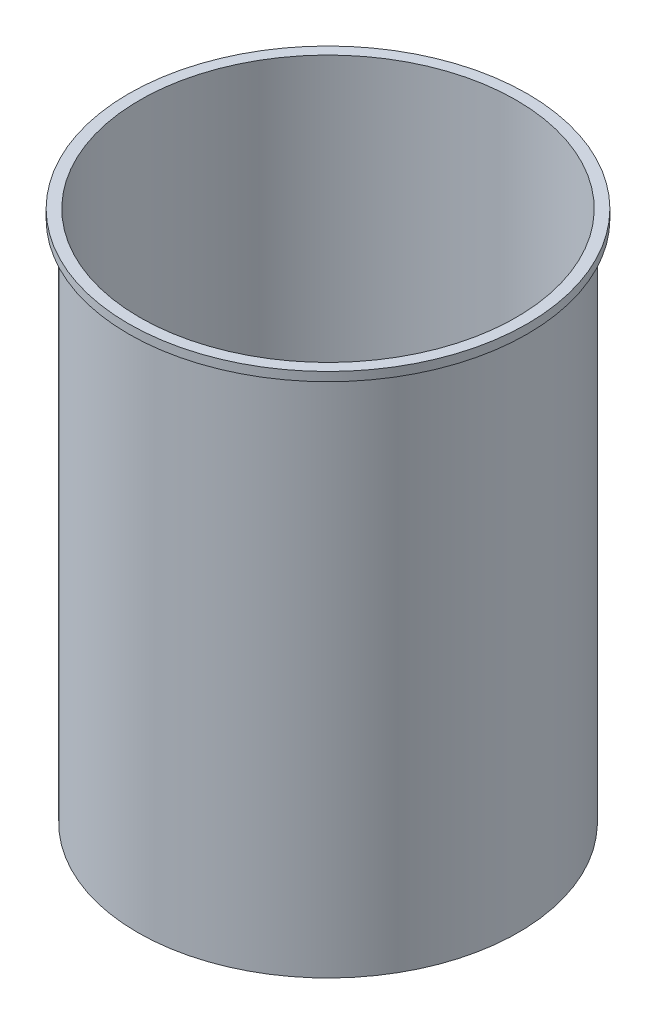
SolidWorks part; units mm, degrees
ref_plane "Front Plane" through (0, 0, 0) normal (0, 0, 1) x (1, 0, 0)
ref_plane "Top Plane" through (0, 0, 0) normal (0, 1, 0) x (1, 0, 0)
ref_plane "Right Plane" through (0, 0, 0) normal (1, 0, 0) x (0, 0, -1)
sketch "Sketch1" plane through (0, 0, 0) normal (0, 1, 0) x (1, 0, 0)
  circle A0 centre (0, 0) radius 42.5
  circle A1 centre (0, 0) radius 43
  dimension "D1" = 85
  dimension "D2" = 0.5
extrude "Boss-Extrude1" add sketch "Sketch1" along normal blind 118
sketch "Sketch2" plane through (0, 118, 0) normal (0, 1, 0) x (1, 0, 0)
  circle A0 centre (0, 0) radius 45
  circle A1 centre (0, 0) radius 42.5
  dimension "D1" = 90
extrude "Boss-Extrude3" add sketch "Sketch2" along normal blind 2
